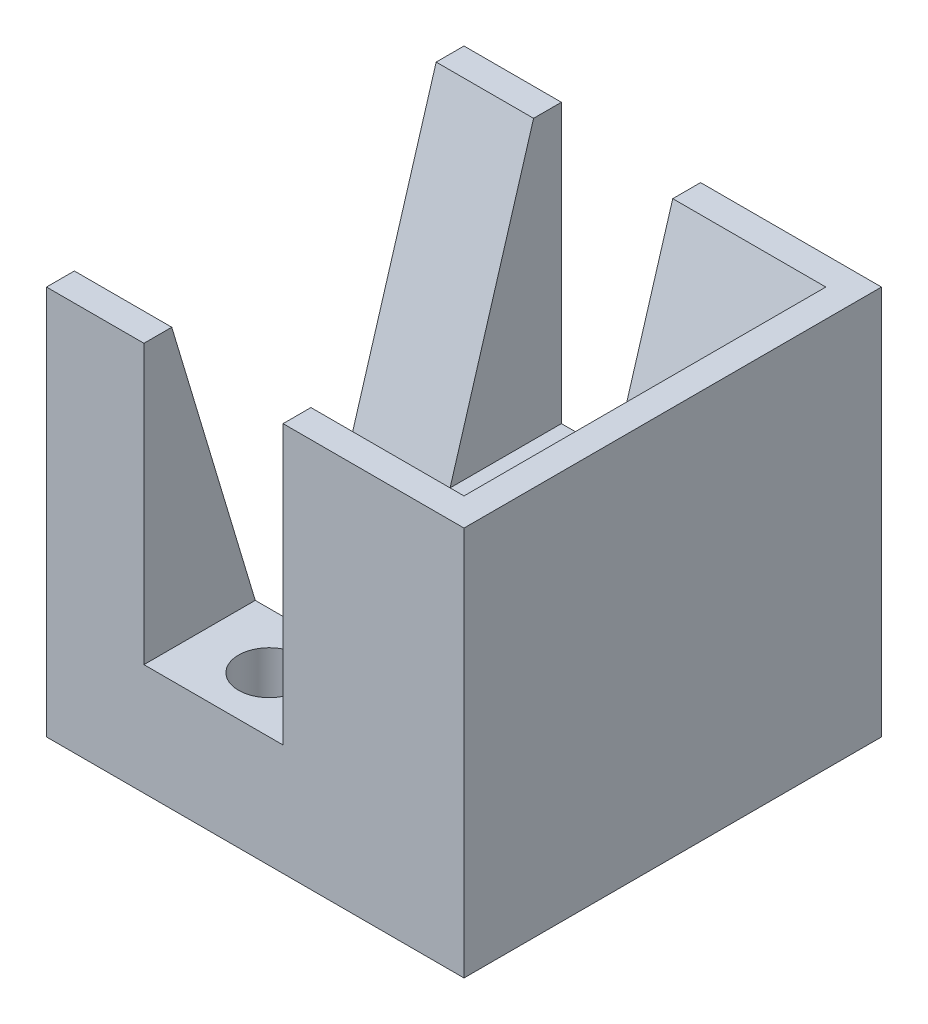
SolidWorks part; units mm, degrees
ref_plane "前视基准面" through (0, 0, 0) normal (0, 0, 1) x (1, 0, 0)
ref_plane "上视基准面" through (0, 0, 0) normal (0, 1, 0) x (1, 0, 0)
ref_plane "右视基准面" through (0, 0, 0) normal (1, 0, 0) x (0, 0, -1)
sketch "草图1" plane through (0, 0, 0) normal (0, 1, 0) x (1, 0, 0)
  line L1 (-5, 2) -> (5, 2)
  line L2 (-5, 2) -> (-5, -2)
  line L3 (-5, -2) -> (5, -2)
  line L4 (5, 2) -> (5, -2)
  line L5 (-5, 2) -> (5, -2) construction
  line L6 (-5, -2) -> (5, 2) construction
  point P0 (0, 0)
  dimension "D1" = 4
  dimension "D2" = 10
extrude "凸台-拉伸1" add sketch "草图1" along normal blind 4
sketch "草图2" plane through (0, 4, 0) normal (0, 1, 0) x (1, 0, 0)
  line L1 (5, 2) -> (10, 2)
  line L2 (5, 2) -> (5, -9)
  line L3 (5, -9) -> (10, -9)
  line L4 (10, 2) -> (10, -9)
  dimension "D1" = 11
  dimension "D2" = 5
extrude "凸台-拉伸2" add sketch "草图2" against normal up to surface (4 mm away) up to face at (0, 0, 0)
sketch "草图3" plane through (0, 4, 0) normal (0, 1, 0) x (1, 0, 0)
  line L1 (10, -9) -> (-5, -9)
  line L2 (10, -9) -> (10, -13)
  line L3 (10, -13) -> (-5, -13)
  line L4 (-5, -9) -> (-5, -13)
  dimension "D1" = 4
  dimension "D2" = 15
extrude "凸台-拉伸3" add sketch "草图3" against normal up to surface (4 mm away) up to face at (3.3333, 0, 3)
sketch "草图4" plane through (0, 4, 0) normal (0, 1, 0) x (1, 0, 0)
  line L0 (-5, 0) -> (1, 0) construction
  line L1 (-5, 2) -> (-5, -2) construction
  line L2 (-5, -11) -> (1, -11) construction
  line L3 (-5, -9) -> (-5, -13) construction
  line L4 (5, -5.5) -> (10, -5.5) construction
  line L5 (5, -2) -> (5, -9) construction
  line L6 (10, -13) -> (10, 2) construction
  circle A0 centre (1, -11) radius 1.1
  circle A1 centre (1, 0) radius 1.1
  dimension "D3" = 2.2
  dimension "D4" = 2.2
  dimension "D1" = 6
  dimension "D2" = 6
extrude "切除-拉伸1" cut sketch "草图4" against normal through all
sketch "草图5" plane through (0, 4, 0) normal (0, 1, 0) x (1, 0, 0)
  line L1 (-5, -13) -> (-1.5, -13)
  line L2 (-5, -13) -> (-5, -9)
  line L3 (-5, -9) -> (-1.5, -9)
  line L4 (-1.5, -13) -> (-1.5, -9)
  line L5 (5, -9) -> (-5, -9) construction
  line L7 (-5, -2) -> (-1.5, -2)
  line L8 (-5, -2) -> (-5, 2)
  line L9 (-5, 2) -> (-1.5, 2)
  line L10 (-1.5, -2) -> (-1.5, 2)
  dimension "D1" = 4
  dimension "D2" = 3.5
  dimension "D3" = 4
  dimension "D4" = 3.5
extrude "凸台-拉伸6" add sketch "草图5" along normal blind 10
sketch "草图8" plane through (-5, 0, 0) normal (-1, 0, 0) x (0, 0, 1)
  line L0 (-2, 14) -> (-1, 14) construction
  line L3 (-1, 14) -> (2, 4) construction
  line L4 (2, 4) -> (-1, 14)
  line L5 (-1, 14) -> (2, 14)
  line L6 (2, 14) -> (2, 0) construction
  line L7 (2, 14) -> (2, 4)
  line L8 (12, 14) -> (9, 4)
  line L10 (9, 4) -> (9, 14)
  line L11 (9, 14) -> (12, 14)
  dimension "D1" = 1
  dimension "D2" = 1
sketch "草图9" plane through (0, 4, 0) normal (0, 1, 0) x (1, 0, 0)
  line L0 (1, 0) -> (3.5, 0) construction
  line L1 (3.5, 0) -> (3.5, 2) construction
  line L2 (10, 2) -> (-1.5, 2) construction
  line L4 (3.5, 2) -> (10, 2)
  line L5 (3.5, 2) -> (3.5, -2)
  line L6 (3.5, -2) -> (10, -2)
  line L7 (10, 2) -> (10, -2)
  line L8 (10, -13) -> (10, 2) construction
  line L9 (1, -11) -> (3.5, -11) construction
  line L10 (3.5, -11) -> (3.5, -13) construction
  line L11 (-1.5, -13) -> (10, -13) construction
  line L13 (3.5, -13) -> (10, -13)
  line L14 (3.5, -13) -> (3.5, -9)
  line L15 (3.5, -9) -> (10, -9)
  line L16 (10, -13) -> (10, -9)
  dimension "D1" = 2.5
  dimension "D2" = 4
  dimension "D3" = 6.5
  dimension "D4" = 2.5
  dimension "D5" = 4
  dimension "D6" = 6.5
extrude "凸台-拉伸7" add sketch "草图9" along normal blind 10
sketch "草图11" plane through (0, 4, 0) normal (0, 1, 0) x (1, 0, 0)
  line L0 (5, -2) -> (10, -2) construction
  line L1 (10, -9) -> (5, -9)
  line L2 (10, -9) -> (10, -2)
  line L3 (10, -2) -> (5, -2)
  line L4 (5, -9) -> (5, -2)
extrude "凸台-拉伸8" add sketch "草图11" along normal blind 10
extrude "切除-拉伸3" cut sketch "草图8" against normal up to surface (10 mm away) up to face at (5, 7, 5.5)
chamfer "倒角2" distance 10 distance2 4 1 edges at (5, 14, 5.5)
